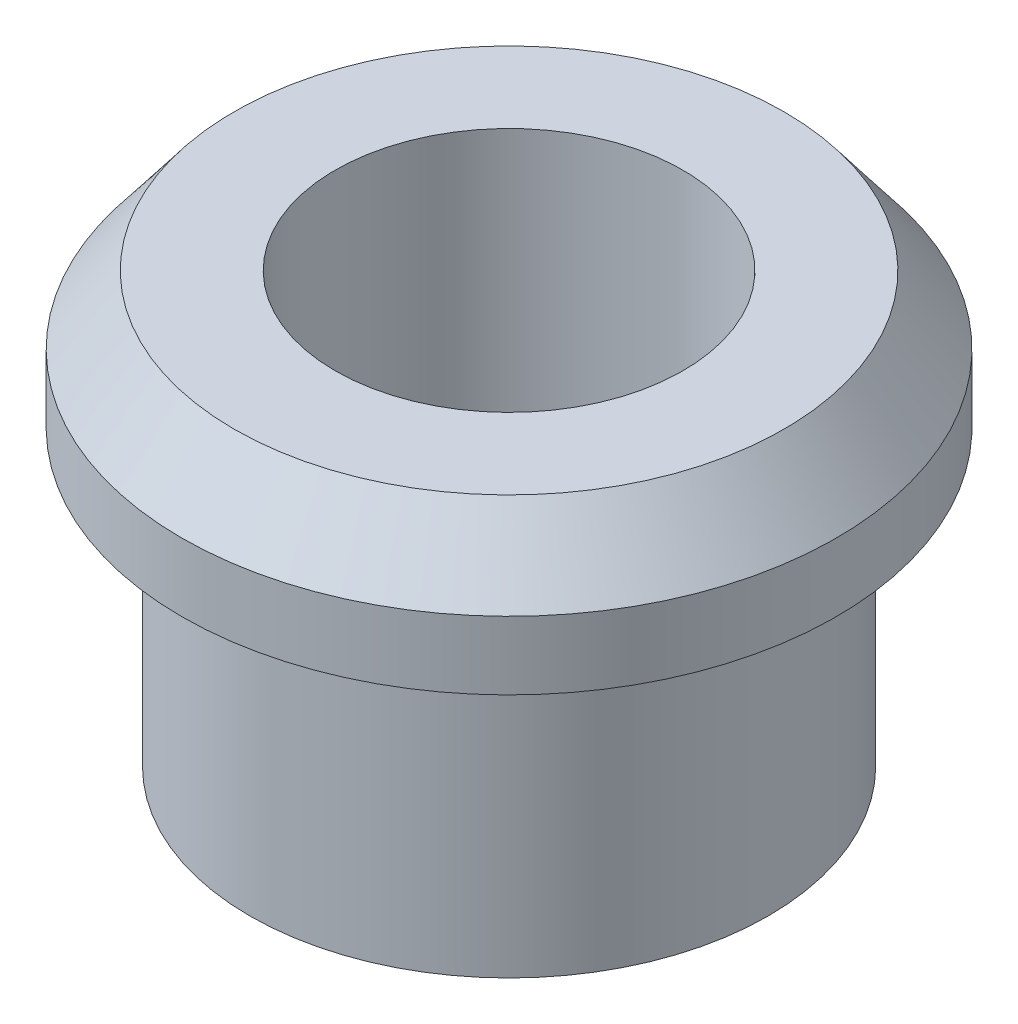
SolidWorks part; units mm, degrees
ref_plane "Front Plane" through (0, 0, 0) normal (0, 0, 1) x (1, 0, 0)
ref_plane "Top Plane" through (0, 0, 0) normal (0, 1, 0) x (1, 0, 0)
ref_plane "Right Plane" through (0, 0, 0) normal (1, 0, 0) x (0, 0, -1)
sketch "Sketch1" plane through (0, 0, 0) normal (0, 0, 1) x (1, 0, 0)
  line L1 (6.2865, -4.9157) -> (6.2865, 2.1963)
  line L2 (6.2865, 2.1963) -> (7.9375, 2.1963)
  line L3 (7.9375, 2.1963) -> (7.9375, 3.8473)
  line L4 (7.9375, 3.8473) -> (6.6675, 5.4983)
  line L5 (6.6675, 5.4983) -> (0, 5.4983)
  line L10 (0, 5.4983) -> (0, -4.9157)
  line L11 (0, -4.9157) -> (6.2865, -4.9157)
  dimension "D1" = 6.2865
  dimension "D2" = 7.112
  dimension "D3" = 1.651
  dimension "D4" = 1.651
  dimension "D5" = 6.6675
  dimension "D6" = 7.9375
revolve "Revolve1" add sketch "Sketch1" angle 360 about L10
hole_wizard "3/8-24 Tapped Hole1" positions "Sketch4" profile "Sketch3" tap size "3/8-24" standard "ANSI Inch" end condition through all
sketch "Sketch4" plane through (0, 5.4983, 0) normal (0, 1, 0) x (1, 0, 0)
  point P0 (0, 0)
sketch "Sketch3" plane through (0, 5.4983, 0) normal (1, 0, 0) x (0, 0, 1)
  line L0 (0, 0) -> (0, 10.414)
  line L1 (0, 10.414) -> (4.2164, 10.414)
  line L2 (4.2164, 10.414) -> (4.2164, 0)
  line L5 (4.2164, 0) -> (0, 0)
  line L11 (0, -6.35) -> (0, 107.95) construction
  dimension "Thru Tap Drill Dia." = 8.4328
  dimension "Thru Tap Drill Depth" = 10.414
cosmetic thread "Hole Thread1" parameters "D2"=9.525
